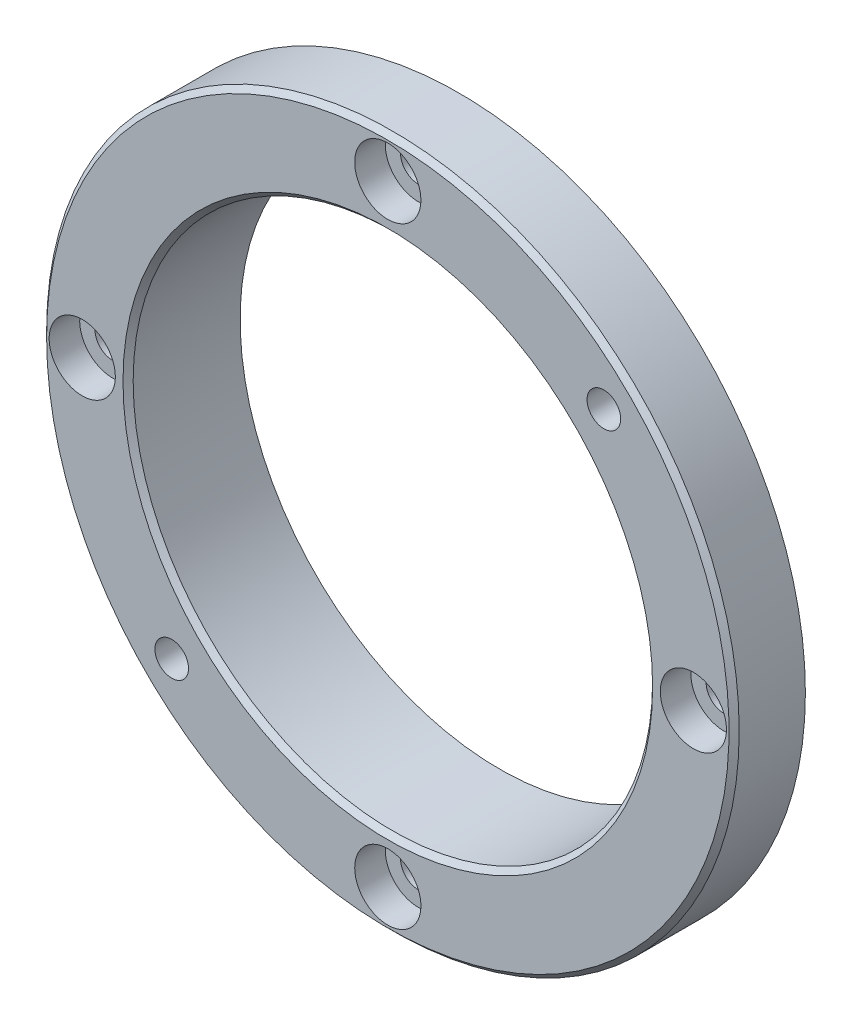
SolidWorks part; units mm, degrees
ref_plane "前基準面" through (0, 0, 0) normal (0, 0, 1) x (1, 0, 0)
ref_plane "上基準面" through (0, 0, 0) normal (0, 1, 0) x (1, 0, 0)
ref_plane "右基準面" through (0, 0, 0) normal (1, 0, 0) x (0, 0, -1)
sketch "草圖1" plane through (0, 0, 0) normal (1, 0, 0) x (0, 0, -1)
  line L0 (0, 0) -> (37.1228, 0) construction
  line L1 (0, 25.5) -> (0, 34)
  line L2 (0, 34) -> (7, 34)
  line L3 (7, 34) -> (7, 27)
  line L4 (7, 27) -> (11, 27)
  line L5 (11, 27) -> (11, 25.5)
  line L6 (11, 25.5) -> (0, 25.5)
  line L7 (0, 25.5) -> (0, 0) construction
  dimension "D1" = 51
  dimension "D2" = 68
  dimension "D3" = 54
  dimension "D4" = 4
  dimension "D5" = 11
revolve "旋轉1" add sketch "草圖1" angle 360 about L0
hole_wizard "M4 螺紋孔1" positions "草圖3" profile "草圖2" tap size "M4" standard "ISO" end condition up to next
sketch "草圖3" plane through (0, 0, 0) normal (0, 0, 1) x (1, 0, 0)
  line L0 (0, 0) -> (19.4503, 0) construction
  line L2 (21.2132, 21.2132) -> (-21.2132, -21.2132) construction
  circle A0 centre (0, 0) radius 30 construction
  point P0 (21.2132, 21.2132)
  point P1 (-21.2132, -21.2132)
  dimension "D2" = 60
  dimension "D1" = 45
sketch "草圖2" plane through (21.2132, 21.2132, 0) normal (1, 0, 0) x (0, -1, 0)
  line L0 (0, 0) -> (0, 7)
  line L1 (0, 7) -> (1.65, 7)
  line L2 (1.65, 7) -> (1.65, 0)
  line L5 (1.65, 0) -> (0, 0)
  line L11 (0, -6.35) -> (0, 107.95) construction
  dimension "貫穿螺孔鑽直徑" = 3.3
  dimension "貫穿螺孔鑽深度" = 7
cosmetic thread "鑽孔螺紋1" parameters "D2"=4
cosmetic thread "鑽孔螺紋2" parameters "D2"=4
sketch "草圖4" plane through (0, 0, 0) normal (0, 0, 1) x (1, 0, 0)
  circle A0 centre (0, 30) radius 3.25
  circle A1 centre (0, 0) radius 30 construction
  dimension "D1" = 6.5
extrude "伸長1" cut sketch "草圖4" against normal blind 3
sketch "草圖5" plane through (0, 0, -3) normal (0, 0, 1) x (1, 0, 0)
  circle A0 centre (0, 30) radius 1.75
  dimension "D1" = 3.5
extrude "伸長2" cut sketch "草圖5" against normal through all
pattern_circular "環狀複製排列1" count 4 over 360 about axis through (0, 0, 0) along (0, 0, 1) of "伸長1", "伸長2"
chamfer "導角1" distance 0.5 angle 45 3 edges at (27, 0, -11) (25.5, 0, 0) (34, 0, 0)
